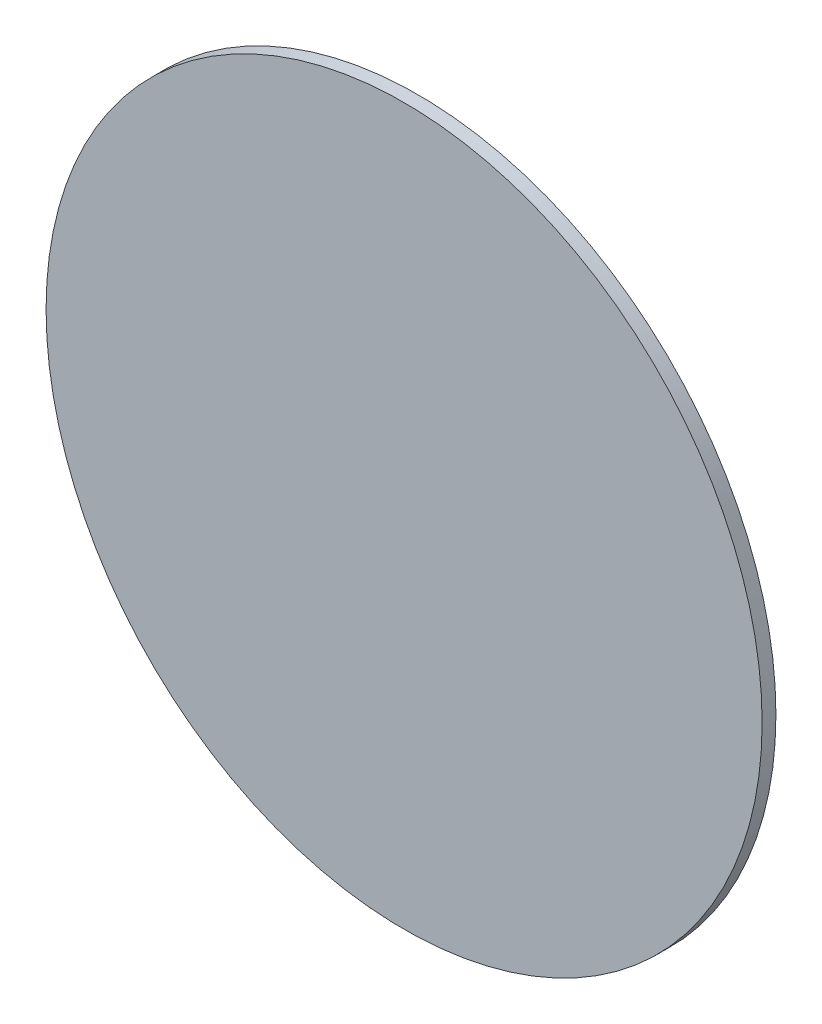
SolidWorks part; units mm, degrees
ref_plane "Front Plane" through (0, 0, 0) normal (0, 0, 1) x (1, 0, 0)
ref_plane "Top Plane" through (0, 0, 0) normal (0, 1, 0) x (1, 0, 0)
ref_plane "Right Plane" through (0, 0, 0) normal (1, 0, 0) x (0, 0, -1)
sketch "Sketch1" plane through (0, 0, 0) normal (0, 0, 1) x (1, 0, 0)
  circle A0 centre (0, 0) radius 82.5
  dimension "D1" = 165
extrude "Boss-Extrude1" add sketch "Sketch1" along normal blind 3.175
